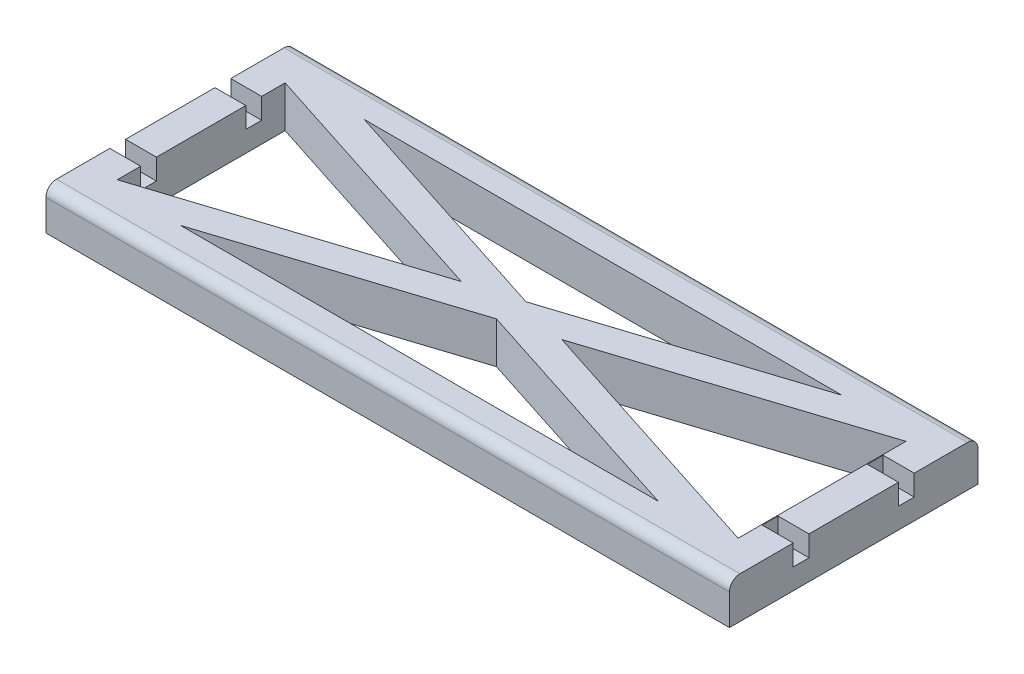
SolidWorks part; units mm, degrees
ref_plane "Front Plane" through (0, 0, 0) normal (0, 0, 1) x (1, 0, 0)
ref_plane "Top Plane" through (0, 0, 0) normal (0, 1, 0) x (1, 0, 0)
ref_plane "Right Plane" through (0, 0, 0) normal (1, 0, 0) x (0, 0, -1)
sketch "Sketch1" plane through (0, 0, 0) normal (0, 1, 0) x (1, 0, 0)
  line L5 (82.5, -30) -> (-82.5, 30) construction
  line L6 (82.5, 30) -> (-82.5, -30) construction
  line L62 (-82.5, 30) -> (-82.5, -30)
  line L63 (-82.5, -30) -> (82.5, -30)
  line L64 (82.5, -30) -> (82.5, 30)
  line L65 (82.5, 30) -> (-82.5, 30)
  line L76 (-82.5, 0) -> (82.5, 0) construction
  line L89 (-75.04, 20.2624) -> (-75.04, -20.2624)
  line L90 (-75.04, -20.2624) -> (-12.2265, 0)
  line L91 (-75.04, 20.2624) -> (-12.2265, 0)
  line L92 (57.4605, 22.1658) -> (-57.8346, 22.1658)
  line L93 (-57.8346, 22.1658) -> (-0.1871, 3.5699)
  line L94 (-0.1871, 3.5699) -> (57.4605, 22.1658)
  line L95 (74.8529, 20.2624) -> (74.8529, -20.2624)
  line L96 (74.8529, -20.2624) -> (12.0394, 0)
  line L97 (74.8529, 20.2624) -> (12.0394, 0)
  line L98 (-57.8346, -22.1658) -> (-0.1871, -3.5699)
  line L99 (-0.1871, -3.5699) -> (57.4605, -22.1658)
  line L100 (-57.8346, -22.1658) -> (57.4605, -22.1658)
  point P0 (0, 0)
  point P6 (-72.5, 16.7742)
  point P10 (-20.5, 0)
  point P16 (72.3129, 16.7742)
  point P20 (-0.1871, 6.2387)
  point P21 (20.3129, 0)
  point P22 (0, -6.6129)
  point P26 (-41.6871, 19.6258)
  point P27 (-72.5, -16.7742)
  point P30 (41.3129, 19.6258)
  dimension "D1" = 60
  dimension "D2" = 165
extrude "Boss-Extrude1" add sketch "Sketch1" along normal blind 10
sketch "Sketch2" plane through (-82.5, 0, 0) normal (-1, 0, 0) x (0, 0, 1)
  line L1 (-30, 10) -> (30, 10) construction
  line L3 (0, 10) -> (0, -1.6306) construction
  line L6 (-14.605, 10) -> (-10.795, 10)
  line L10 (14.605, 10) -> (10.795, 10)
  line L18 (-14.605, 10) -> (-14.605, 5)
  line L19 (-10.795, 5) -> (-10.795, 10)
  line L20 (-30, 0) -> (30, 0) construction
  line L22 (10.795, 10) -> (10.795, 5)
  line L24 (14.605, 10) -> (14.605, 5)
  line L26 (-10.795, 5) -> (-14.605, 5)
  line L27 (14.605, 5) -> (10.795, 5)
  point P8 (0, 2.5)
  point P25 (-12.7, 5)
  point P28 (12.7, 5)
  dimension "D1" = 5
  dimension "D2" = 3.81
  dimension "D3" = 5
  dimension "D4" = 21.59
extrude "Cut-Extrude1" cut sketch "Sketch2" against normal blind 7.5
sketch "Sketch3" plane through (0, 10, 0) normal (0, 1, 0) x (1, 0, 0)
  line L0 (0, 0) -> (0, 30) construction
  line L1 (82.5, 30) -> (-82.5, 30) construction
mirror "Mirror1" about plane through (0, 0, 0) normal (1, 0, 0) of "Cut-Extrude1"
fillet "Fillet1" radius 2.54 2 edges at (0, 10, 30) (0, 10, -30)
